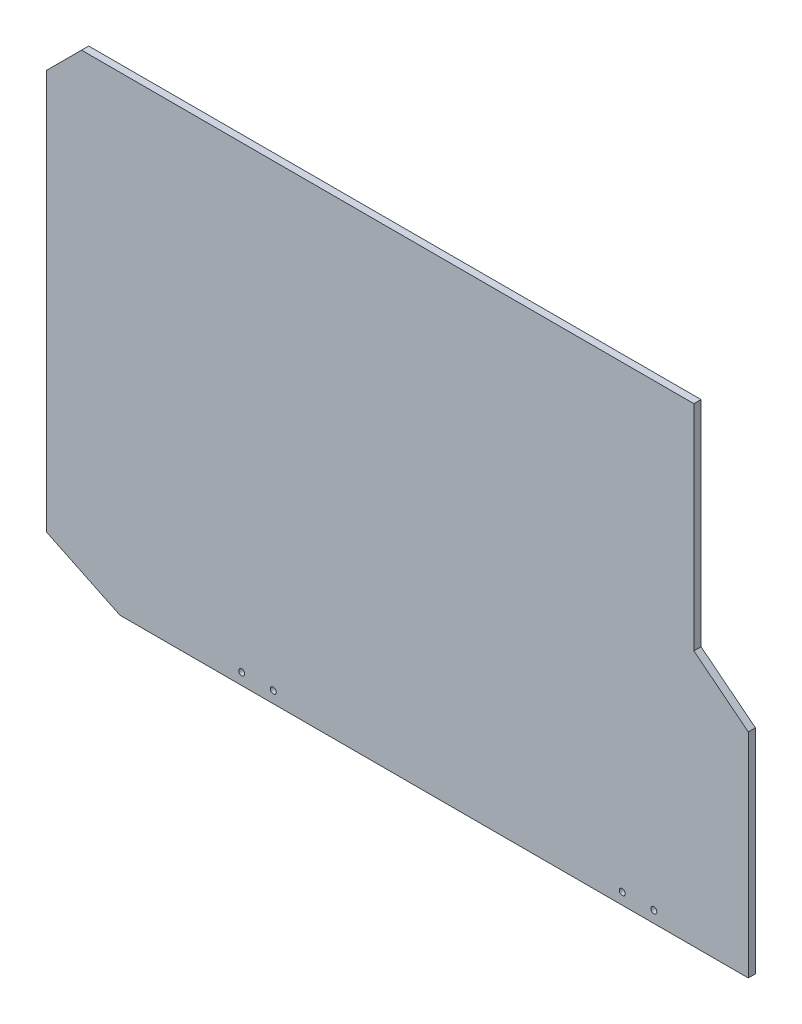
SolidWorks part; units mm, degrees
ref_plane "Plan de face" through (0, 0, 0) normal (0, 0, 1) x (1, 0, 0)
ref_plane "Plan de dessus" through (0, 0, 0) normal (0, 1, 0) x (1, 0, 0)
ref_plane "Plan de droite" through (0, 0, 0) normal (1, 0, 0) x (0, 0, -1)
sketch "Esquisse1" plane through (0, 0, 0) normal (0, 0, 1) x (1, 0, 0)
  line L0 (21.5, 22) -> (-30.5, 47) construction
  line L1 (21.5, 22) -> (461.5, 22) construction
  line L2 (461.5, 22) -> (461.5, 172.3) construction
  line L3 (423.5, 202.3) -> (461.5, 172.3) construction
  line L4 (423.5, 352.3) -> (423.5, 202.3) construction
  line L5 (423.5, 352.3) -> (-5.5, 352.3) construction
  line L6 (-30.5, 327.3) -> (-5.5, 352.3) construction
  line L7 (-30.5, 327.3) -> (-30.5, 47) construction
  line L8 (21.5, 22) -> (-30.5, 47) construction
  line L9 (21.5, 22) -> (461.5, 22) construction
  line L10 (461.5, 22) -> (461.5, 172.3) construction
  line L11 (423.5, 202.3) -> (461.5, 172.3) construction
  line L12 (423.5, 352.3) -> (423.5, 202.3) construction
  line L13 (423.5, 352.3) -> (-5.5, 352.3) construction
  line L14 (-30.5, 327.3) -> (-5.5, 352.3) construction
  line L15 (-30.5, 327.3) -> (-30.5, 47) construction
  line L16 (-29.5, 326.8858) -> (-29.5, 47.6288)
  line L17 (21.7279, 23) -> (-29.5, 47.6288)
  line L18 (21.7279, 23) -> (460.5, 23)
  line L19 (460.5, 23) -> (460.5, 171.8154)
  line L20 (422.5, 201.8154) -> (460.5, 171.8154)
  line L21 (422.5, 351.3) -> (422.5, 201.8154)
  line L22 (422.5, 351.3) -> (-5.0858, 351.3)
  line L23 (-29.5, 326.8858) -> (-5.0858, 351.3)
  dimension "D1" = 1
extrude "Boss.-Extru.1" add sketch "Esquisse1" against normal blind 5
sketch "Esquisse3" plane through (0, 0, 0) normal (0, 0, 1) x (1, 0, 0)
  line L0 (-75.5617, 31) -> (531.2821, 31) construction
  line L1 (21.7279, 23) -> (460.5, 23) construction
  line L2 (-29.5, 326.8858) -> (-29.5, 47.6288) construction
  line L4 (460.5, 23) -> (460.5, 171.8154) construction
  circle A0 centre (106.8, 31) radius 2.1
  circle A1 centre (128.8, 31) radius 2.1
  circle A2 centre (372.5, 31) radius 2.1
  circle A3 centre (394.5, 31) radius 2.1
  dimension "D2" = 4.2
  dimension "D3" = 4.2
  dimension "D4" = 22
  dimension "D5" = 136.3
  dimension "D6" = 66
  dimension "D7" = 22
  dimension "D8" = 4.2
  dimension "D9" = 4.2
  dimension "D1" = 8
extrude "Enlèv. mat.-Extru.2" cut sketch "Esquisse3" against normal through all
